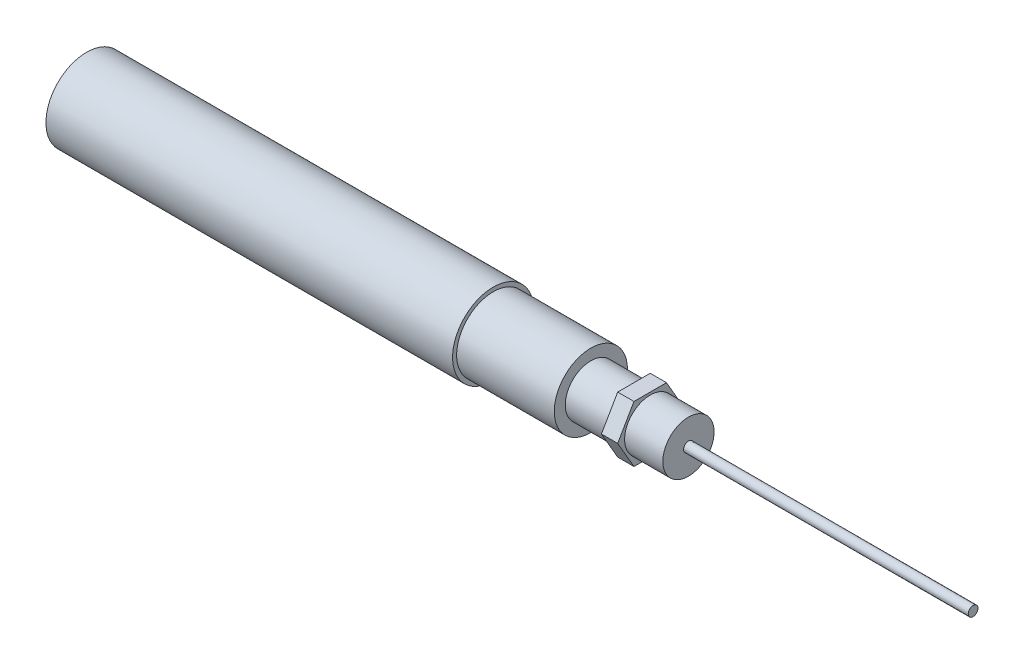
SolidWorks part; units mm, degrees
ref_plane "Front Plane" through (0, 0, 0) normal (0, 0, 1) x (1, 0, 0)
ref_plane "Top Plane" through (0, 0, 0) normal (0, 1, 0) x (1, 0, 0)
ref_plane "Right Plane" through (0, 0, 0) normal (1, 0, 0) x (0, 0, -1)
sketch "SK SMA body" plane through (0, 0, 0) normal (1, 0, 0) x (0, 0, -1)
  circle A0 centre (0, 0) radius 3.15
extrude "SMA body" add sketch "SK SMA body" along normal blind 12 from offset 2 separate body
sketch "SK SMA nut" plane through (0, 0, 0) normal (1, 0, 0) x (0, 0, -1)
  line L1 (4, 0) -> (2, 3.4641)
  line L2 (2, 3.4641) -> (-2, 3.4641)
  line L3 (-2, 3.4641) -> (-4, 0)
  line L4 (-4, 0) -> (-2, -3.4641)
  line L5 (-2, -3.4641) -> (2, -3.4641)
  line L6 (2, -3.4641) -> (4, 0)
  circle A0 centre (0, 0) radius 3.15
  circle A1 centre (0, 0) radius 3.4641 construction
extrude "SMA nut" add sketch "SK SMA nut" along normal blind 2 from offset 3.3 separate body
sketch "SK Antenna base" plane through (0, 0, 0) normal (1, 0, 0) x (0, 0, -1)
  circle A0 centre (0, 0) radius 4.5
extrude "Antenna base" add sketch "SK Antenna base" along normal blind 12 from offset 14 separate body
sketch "SK Antenna" plane through (0, 0, 0) normal (1, 0, 0) x (0, 0, -1)
  circle A0 centre (0, 0) radius 5
extrude "Antenna" add sketch "SK Antenna" along normal blind 50 from offset 64 separate body
sketch "SK uFL pigtail" plane through (0, 0, 0) normal (1, 0, 0) x (0, 0, -1)
  circle A0 centre (0, 0) radius 0.6
extrude "uFL pigtail" add sketch "SK uFL pigtail" along normal blind 35 from offset 10 separate body
